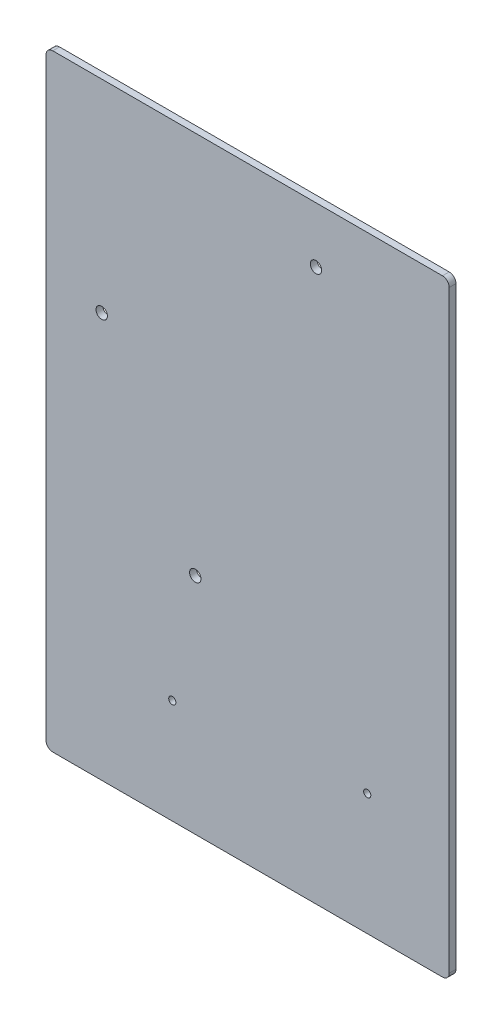
SolidWorks part; units mm, degrees
material "PC High Viscosity"
ref_plane "Front Plane" through (0, 0, 0) normal (0, 0, 1) x (1, 0, 0)
ref_plane "Top Plane" through (0, 0, 0) normal (0, 1, 0) x (1, 0, 0)
ref_plane "Right Plane" through (0, 0, 0) normal (1, 0, 0) x (0, 0, -1)
sketch "Sketch1" plane through (0, 0, 0) normal (0, 0, 1) x (1, 0, 0)
  line L0 (0, 0) -> (0, 571.5)
  line L1 (0, 0) -> (379.4125, 0)
  line L2 (381, 355.6) -> (425.45, 355.6) construction
  line L3 (381, 355.6) -> (381, 400.05) construction
  line L4 (381, 400.05) -> (425.45, 400.05) construction
  line L5 (425.45, 355.6) -> (425.45, 400.05) construction
  line L6 (379.4125, 0) -> (379.4125, 403.225)
  line L7 (379.4125, 403.225) -> (428.625, 403.225)
  line L8 (428.625, 403.225) -> (428.625, 355.6)
  line L9 (428.625, 355.6) -> (479.425, 355.6)
  line L10 (479.425, 355.6) -> (479.425, 466.725)
  line L12 (379.4125, 571.5) -> (0, 571.5)
  line L13 (379.4125, 571.5) -> (379.4125, 466.725)
  line L14 (379.4125, 466.725) -> (479.425, 466.725)
  dimension "D1" = 571.5
  dimension "D2" = 44.45
  dimension "D3" = 400.05
  dimension "D4" = 381
  dimension "D5" = 3.175
  dimension "D6" = 3.175
  dimension "D7" = 3.175
  dimension "D8" = 50.8
  dimension "D9" = 63.5
extrude "Boss-Extrude1" add sketch "Sketch1" along normal blind 6.35
fillet "Fillet1" radius 3.175 2 edges at (428.625, 403.225, 3.175) (379.4125, 403.225, 3.175)
fillet "Fillet2" radius 44.45 2 edges at (479.425, 466.725, 3.175) (379.4125, 466.725, 3.175)
hole_wizard "1/4 Clearance Hole1" positions "Sketch2" profile "Sketch3" hole size "1/4" standard "ANSI Inch" end condition through all
sketch "Sketch2" plane through (0, 0, 0) normal (0, 0, -1) x (-1, 0, 0)
  line L0 (0, 77.4886) -> (-379.4125, 110.6829) construction
  line L1 (0, 571.5) -> (0, 0) construction
  line L2 (-379.4125, 0) -> (-379.4125, 400.05) construction
  line L4 (0, 0) -> (-379.4125, 0) construction
  line L5 (-320.0116, 93.5432) -> (-104.9332, 74.7262) construction
  line L6 (-320.0116, 93.5432) -> (-316.691, 131.4982) construction
  line L7 (-104.9332, 74.7262) -> (-101.6126, 112.6813) construction
  line L8 (-316.691, 131.4982) -> (-101.6126, 112.6813) construction
  line L9 (-319.8049, 95.9065) -> (-104.7264, 77.0896) construction
  line L11 (0, 0) -> (-44.45, 0) construction
  line L12 (0, 0) -> (0, 571.5) construction
  line L13 (0, 571.5) -> (-44.45, 571.5) construction
  line L14 (-44.45, 0) -> (-44.45, 571.5) construction
  line L15 (-379.4125, 571.5) -> (0, 571.5) construction
  line L17 (-381, 0) -> (-425.45, 0) construction
  line L18 (-381, 0) -> (-381, 571.5) construction
  line L19 (-381, 571.5) -> (-425.45, 571.5) construction
  line L20 (-425.45, 0) -> (-425.45, 571.5) construction
  line L21 (-379.4125, 121.05) -> (-44.45, 91.7445) construction
  line L23 (-209.1518, 122.0897) -> (-212.4724, 84.1347) construction
  line L24 (-318.9747, 105.3953) -> (-103.8963, 86.5783) construction
  line L25 (-319.6665, 97.488) -> (-104.5881, 78.671) construction
  line L27 (-104.4497, 80.2525) -> (-319.5281, 99.0694) construction
  line L28 (-425.45, 44.45) -> (0, 44.45) construction
  point P0 (-118.8107, 98.2503)
  point P2 (-302.26, 114.3)
  point P213 (-209.1518, 122.0897)
  dimension "D2" = 5
  dimension "D3" = 2.3724
  dimension "D4" = 38.1
  dimension "D5" = 215.9
  dimension "D6" = 44.45
  dimension "D7" = 0
  dimension "D8" = 381
  dimension "D9" = 15.875
  dimension "D10" = 184.15
  dimension "D11" = 1.5875
  dimension "D12" = 1.5875
  dimension "D13" = 6.35
  dimension "D14" = 44.45
  dimension "D15" = 302.26
  dimension "D16" = 114.3
sketch "Sketch3" plane through (118.8107, 98.2503, 0) normal (1, 0, 0) x (0, 1, 0)
  line L0 (0, 0) -> (0, 6.35)
  line L1 (0, 6.35) -> (3.3782, 6.35)
  line L2 (3.3782, 6.35) -> (3.3782, 0)
  line L5 (3.3782, 0) -> (0, 0)
  line L11 (0, -6.35) -> (0, 107.95) construction
  dimension "Thru Hole Dia." = 6.7564
  dimension "Thru Hole Depth" = 6.35
sketch "Sketch4" plane through (0, 0, 0) normal (0, 0, -1) x (-1, 0, 0)
  line L1 (-379.4125, 511.175) -> (-479.425, 511.175)
  line L2 (-379.4125, 511.175) -> (-379.4125, 355.6)
  line L3 (-379.4125, 355.6) -> (-479.425, 355.6)
  line L4 (-479.425, 511.175) -> (-479.425, 355.6)
extrude "Cut-Extrude1" cut sketch "Sketch4" against normal through all
hole_wizard "27/64 (0.42188) Diameter Hole1" positions "Sketch6" profile "Sketch7" hole size "27/64" standard "ANSI Inch" end condition through all
sketch "Sketch6" plane through (0, 0, 0) normal (0, 0, -1) x (-1, 0, 0)
  line L0 (-44.45, 571.5) -> (-44.45, 0) construction
  line L1 (0, 571.5) -> (0, 0) construction
  line L2 (0, 0) -> (-379.4125, 0) construction
  line L3 (0, 381) -> (-52.3875, 381) construction
  line L4 (-254, 571.5) -> (-254, 519.1125) construction
  line L5 (-379.4125, 571.5) -> (0, 571.5) construction
  line L6 (-379.4125, 571.5) -> (0, 571.5) construction
  line L7 (0, 0) -> (-379.4125, 0) construction
  point P0 (-254, 519.1125)
  point P2 (-52.3875, 381)
  point P4 (-140.462, 210.82)
  point P28 (-44.45, 571.5)
  point P31 (-44.45, 0)
  dimension "D1" = 44.45
  dimension "D2" = 7.9375
  dimension "D3" = 210.82
  dimension "D4" = 381
  dimension "D5" = 254
  dimension "D6" = 140.462
sketch "Sketch7" plane through (254, 519.1125, 0) normal (1, 0, 0) x (0, 1, 0)
  line L0 (0, 0) -> (0, 6.35)
  line L1 (0, 6.35) -> (5.3579, 6.35)
  line L2 (5.3579, 6.35) -> (5.3579, 0)
  line L5 (5.3579, 0) -> (0, 0)
  line L11 (0, -6.35) -> (0, 107.95) construction
  dimension "Thru Hole Dia." = 10.7158
  dimension "Thru Hole Depth" = 6.35
fillet "Fillet3" radius 6.35 4 edges at (379.4125, 0, 3.175) (0, 571.5, 3.175) (379.4125, 571.5, 3.175) (0, 0, 3.175)
